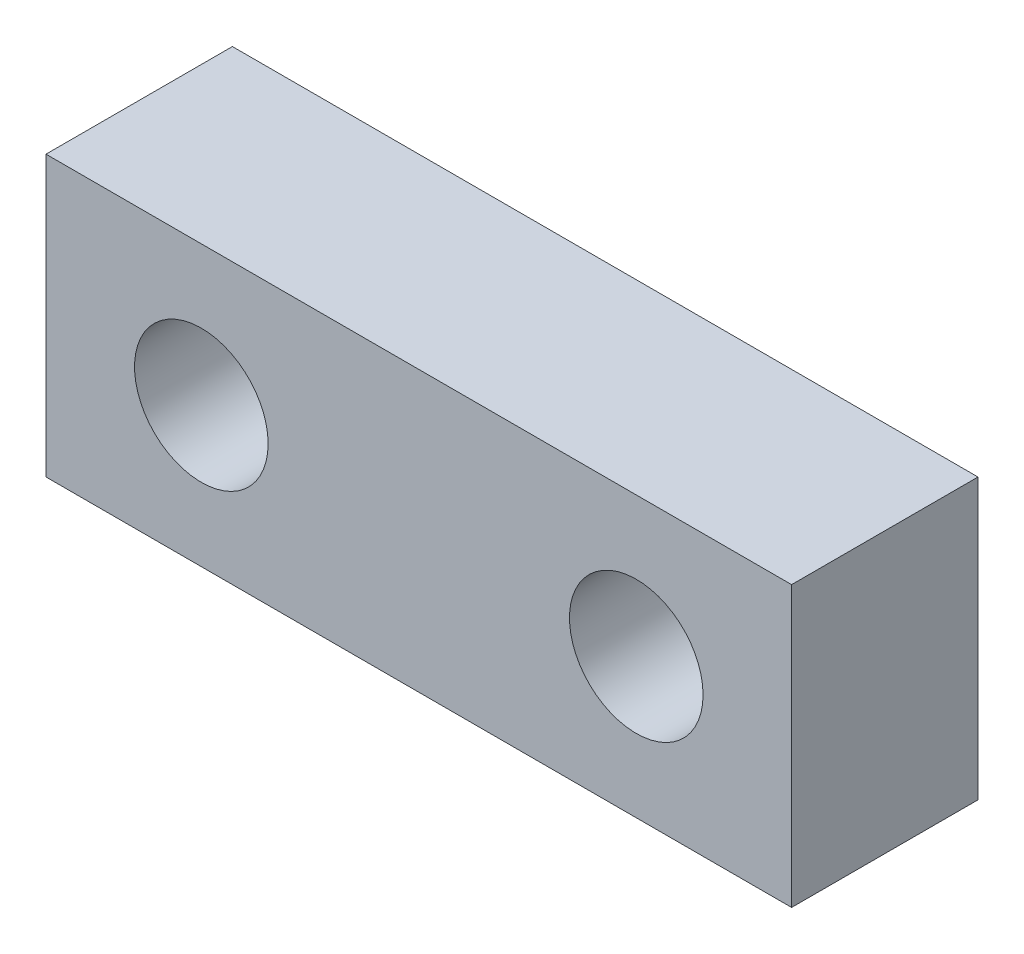
SolidWorks part; units mm, degrees
ref_plane "前视基准面" through (0, 0, 0) normal (0, 0, 1) x (1, 0, 0)
ref_plane "上视基准面" through (0, 0, 0) normal (0, 1, 0) x (1, 0, 0)
ref_plane "右视基准面" through (0, 0, 0) normal (1, 0, 0) x (0, 0, -1)
sketch "草图1" plane through (0, 0, 0) normal (0, 0, 1) x (1, 0, 0)
  line L1 (-60, -22.5) -> (60, -22.5)
  line L2 (-60, -22.5) -> (-60, 22.5)
  line L3 (-60, 22.5) -> (60, 22.5)
  line L4 (60, -22.5) -> (60, 22.5)
  line L5 (-60, -22.5) -> (60, 22.5) construction
  line L6 (-60, 22.5) -> (60, -22.5) construction
  point P0 (0, 0)
  dimension "D1" = 120
  dimension "D2" = 45
extrude "凸台-拉伸1" add sketch "草图1" along normal blind 30
sketch "草图2" plane through (0, 0, 30) normal (0, 0, 1) x (1, 0, 0)
  line L0 (0, 22.5) -> (0, -22.5) construction
  line L1 (60, 22.5) -> (-60, 22.5) construction
  line L2 (-60, -22.5) -> (60, -22.5) construction
  line L3 (-60, 0) -> (60, 0) construction
  line L4 (-60, 22.5) -> (-60, -22.5) construction
  line L5 (60, -22.5) -> (60, 22.5) construction
  circle A0 centre (-35, 0) radius 10.75
  circle A1 centre (35, 0) radius 10.75
  dimension "D1" = 70
  dimension "D2" = 21.5
extrude "切除-拉伸1" cut sketch "草图2" against normal up to next
sketch "草图18" plane through (0, -22.5, 0) normal (0, -1, 0) x (1, 0, 0)
  line L0 (0, 30) -> (0, 0) construction
  line L1 (-60, 30) -> (60, 30) construction
  line L2 (0, 30) -> (-60, 0) construction
  line L3 (-60, 30) -> (0, 0) construction
  line L4 (-40.6066, 25.6066) -> (-19.3934, 25.6066)
  line L5 (-40.6066, 25.6066) -> (-40.6066, 4.3934)
  line L6 (-40.6066, 4.3934) -> (-19.3934, 4.3934)
  line L7 (-19.3934, 25.6066) -> (-19.3934, 4.3934)
  line L8 (-40.6066, 25.6066) -> (-19.3934, 4.3934) construction
  line L9 (-40.6066, 4.3934) -> (-19.3934, 25.6066) construction
  line L10 (40.6066, 4.3934) -> (19.3934, 4.3934)
  line L11 (40.6066, 25.6066) -> (40.6066, 4.3934)
  line L12 (40.6066, 25.6066) -> (19.3934, 25.6066)
  line L13 (19.3934, 25.6066) -> (19.3934, 4.3934)
  circle A0 centre (-30, 15) radius 15
hole_wizard "M3 螺纹孔1" positions "草图21" profile "草图22" tap size "M3" standard "GB"
sketch "草图21" plane through (0, -22.5, 0) normal (0, -1, 0) x (-1, 0, 0)
  point P0 (-40.6066, -4.3934)
  point P3 (-19.3934, -4.3934)
  point P6 (-19.3934, -25.6066)
  point P9 (-40.6066, -25.6066)
  point P12 (19.3934, -4.3934)
  point P15 (40.6066, -4.3934)
  point P18 (19.3934, -25.6066)
  point P21 (40.6066, -25.6066)
sketch "草图22" plane through (40.6066, -22.5, 4.3934) normal (1, 0, 0) x (0, 0, -1)
  line L0 (0, 0) -> (0, 8.2511)
  line L1 (0, 8.2511) -> (1.25, 7.5)
  line L2 (1.25, 7.5) -> (1.25, 0)
  line L5 (1.25, 0) -> (0, 0)
  line L10 (0, 8.2511) -> (-1.25, 7.5) construction
  line L11 (0, -6.35) -> (0, 107.95) construction
  dimension "螺纹孔钻头直径" = 2.5
  dimension "螺纹孔钻头深度" = 7.5
  dimension "导头角度" = 118
cosmetic thread "孔螺蚊线18" parameters "D1"=6, "D2"=3
cosmetic thread "孔螺蚊线19" parameters "D1"=6, "D2"=3
cosmetic thread "孔螺蚊线20" parameters "D1"=6, "D2"=3
cosmetic thread "孔螺蚊线21" parameters "D1"=6, "D2"=3
cosmetic thread "孔螺蚊线22" parameters "D1"=6, "D2"=3
cosmetic thread "孔螺蚊线23" parameters "D1"=6, "D2"=3
cosmetic thread "孔螺蚊线24" parameters "D1"=6, "D2"=3
cosmetic thread "孔螺蚊线25" parameters "D1"=6, "D2"=3
sketch "草图23" plane through (0, 22.5, 0) normal (0, 1, 0) x (1, 0, 0)
  line L0 (-60, 0) -> (60, -30) construction
  line L1 (60, 0) -> (-60, -30) construction
sketch "草图24" plane through (0, 0, 0) normal (0, 0, -1) x (-1, 0, 0)
  line L1 (46.3, 11.3) -> (23.7, 11.3)
  line L2 (46.3, 11.3) -> (46.3, -11.3)
  line L3 (46.3, -11.3) -> (23.7, -11.3)
  line L4 (23.7, 11.3) -> (23.7, -11.3)
  line L5 (46.3, 11.3) -> (23.7, -11.3) construction
  line L6 (46.3, -11.3) -> (23.7, 11.3) construction
  line L7 (-23.7, 11.3) -> (-46.3, 11.3)
  line L8 (-23.7, 11.3) -> (-23.7, -11.3)
  line L9 (-23.7, -11.3) -> (-46.3, -11.3)
  line L10 (-46.3, 11.3) -> (-46.3, -11.3)
  line L11 (-23.7, 11.3) -> (-46.3, -11.3) construction
  line L12 (-23.7, -11.3) -> (-46.3, 11.3) construction
  point P0 (35, 0)
  point P6 (-35, 0)
  dimension "D1" = 22.6
  dimension "D2" = 22.6
  dimension "D3" = 22.6
  dimension "D4" = 22.6
hole_wizard "M4 螺纹孔1" positions "3D草图1" profile "草图25" tap size "M4" standard "ISO"
sketch3d "3D草图1"
  point P0 (-46.3, 11.3, 0)
  point P3 (-46.3, -11.3, 0)
  point P6 (-23.7, -11.3, 0)
  point P9 (-23.7, 11.3, 0)
  point P12 (23.7, 11.3, 0)
  point P15 (23.7, -11.3, 0)
  point P18 (46.3, -11.3, 0)
  point P21 (46.3, 11.3, 0)
sketch "草图25" plane through (-46.3, 11.3, 0) normal (1, 0, 0) x (0, 1, 0)
  line L0 (0, 0) -> (0, 11.0914)
  line L1 (0, 11.0914) -> (1.65, 10.1)
  line L2 (1.65, 10.1) -> (1.65, 0)
  line L5 (1.65, 0) -> (0, 0)
  line L10 (0, 11.0914) -> (-1.65, 10.1) construction
  line L11 (0, -6.35) -> (0, 107.95) construction
  dimension "螺纹孔钻头直径" = 3.3
  dimension "螺纹孔钻头深度" = 10.1
  dimension "导头角度" = 118
cosmetic thread "孔螺蚊线26" parameters "D1"=8, "D2"=4
cosmetic thread "孔螺蚊线27" parameters "D1"=8, "D2"=4
cosmetic thread "孔螺蚊线28" parameters "D1"=8, "D2"=4
cosmetic thread "孔螺蚊线29" parameters "D1"=8, "D2"=4
cosmetic thread "孔螺蚊线30" parameters "D1"=8, "D2"=4
cosmetic thread "孔螺蚊线31" parameters "D1"=8, "D2"=4
cosmetic thread "孔螺蚊线32" parameters "D1"=8, "D2"=4
cosmetic thread "孔螺蚊线33" parameters "D1"=8, "D2"=4
